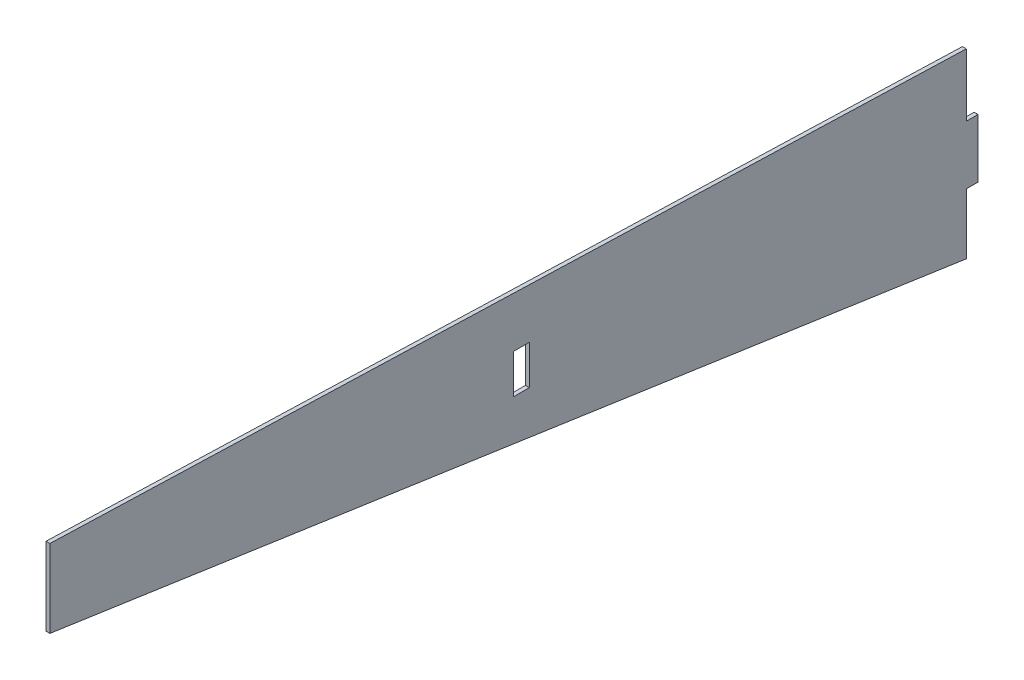
SolidWorks part; units mm, degrees
material "Balsa"
ref_plane "Front Plane" through (0, 0, 0) normal (0, 0, 1) x (1, 0, 0)
ref_plane "Top Plane" through (0, 0, 0) normal (0, 1, 0) x (1, 0, 0)
ref_plane "Right Plane" through (0, 0, 0) normal (1, 0, 0) x (0, 0, -1)
sketch "Sketch1" plane through (0, 0, 0) normal (1, 0, 0) x (0, 0, -1)
  line L0 (0, 0) -> (0, 31.75)
  line L1 (0, 31.75) -> (378.2598, 19.4419)
  line L2 (378.2598, 19.4419) -> (378.2598, -55.2341)
  line L3 (378.2598, -55.2341) -> (0, 0)
  point P4 (0, 0)
  dimension "D1" = 378.46
  dimension "D2" = 31.75
  dimension "D3" = 74.676
extrude "Boss-Extrude1" add sketch "Sketch1" along normal blind 1.5875
sketch "Sketch3" plane through (1.5875, 0, 0) normal (1, 0, 0) x (0, 0, -1)
  line L0 (378.2598, -55.2341) -> (378.2598, -29.8341)
  line L1 (378.2598, -55.2341) -> (378.2598, 19.4419) construction
  line L2 (378.2598, -29.8341) -> (373.4973, -29.8341)
  line L3 (373.4973, -29.8341) -> (373.4973, -54.5387)
  line L4 (0, 0) -> (378.2598, -55.2341) construction
  line L5 (373.4973, -54.5387) -> (378.2598, -55.2341)
  line L6 (378.2598, 19.4419) -> (373.4973, 19.5969)
  line L7 (378.2598, 19.4419) -> (0, 31.75) construction
  line L8 (373.4973, 19.5969) -> (373.4973, -5.9581)
  line L9 (373.4973, -5.9581) -> (378.2598, -5.9581)
  line L10 (378.2598, -5.9581) -> (378.2598, 19.4419)
  dimension "D1" = 25.4
  dimension "D2" = 4.7625
  dimension "D3" = 23.876
extrude "Cut-Extrude2" cut sketch "Sketch3" against normal through all
sketch "Sketch4" plane through (1.5875, 0, 0) normal (1, 0, 0) x (0, 0, -1)
  line L0 (189.0298, 5.0618) -> (189.0298, -10.9402)
  line L1 (189.0298, -10.9402) -> (195.3798, -10.9402)
  line L2 (195.3798, -10.9402) -> (195.3798, 5.0618)
  line L3 (195.3798, 5.0618) -> (189.0298, 5.0618)
  line L4 (378.2598, -29.8341) -> (378.2598, -5.9581) construction
  line L6 (373.4973, 19.5969) -> (0, 31.75) construction
  dimension "D1" = 189.23
  dimension "D2" = 16.002
  dimension "D3" = 20.32
  dimension "D4" = 6.35
extrude "Cut-Extrude3" cut sketch "Sketch4" against normal up to surface (1.5875 mm away) up to face at (0, -9.347, -281.3136)
